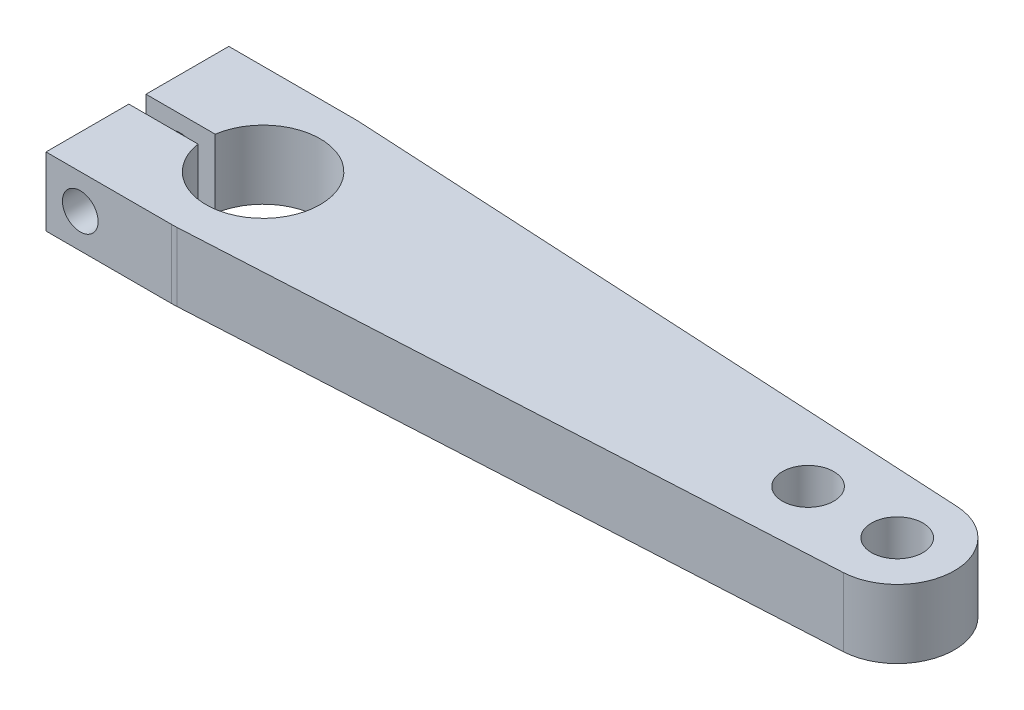
SolidWorks part; units mm, degrees
ref_plane "Alzado" through (0, 0, 0) normal (0, 0, 1) x (1, 0, 0)
ref_plane "Planta" through (0, 0, 0) normal (0, 1, 0) x (1, 0, 0)
ref_plane "Vista lateral" through (0, 0, 0) normal (1, 0, 0) x (0, 0, -1)
sketch "Croquis1" plane through (0, 0, 0) normal (0, 1, 0) x (1, 0, 0)
  line L0 (0.8649, 15.9766) -> (111.5405, 9.9854)
  line L1 (-22, 16) -> (0, 16)
  line L2 (-22, 16) -> (-22, -16)
  line L3 (-22, -16) -> (0, -16)
  line L5 (0.8649, -15.9766) -> (111.5405, -9.9854)
  circle A0 centre (0, 0) radius 10
  arc A1 (111.5405, -9.9854) -> (111.5405, 9.9854) centre (111, 0) ccw
  arc A2 (0.8649, 15.9766) -> (0, 16) centre (0, 0) ccw
  arc A3 (0, -16) -> (0.8649, -15.9766) centre (0, 0) ccw
  dimension "D3" = 20
  dimension "D5" = 10
  dimension "D1" = 16
  dimension "D2" = 16
  dimension "D4" = 22
  dimension "D6" = 111
extrude "Saliente-Extruir1" add sketch "Croquis1" along normal blind 12
sketch "Croquis2" plane through (0, 12, 0) normal (0, 1, 0) x (1, 0, 0)
  line L1 (-6.1165, 1.5) -> (-27.9498, 1.5)
  line L2 (-6.1165, 1.5) -> (-6.1165, -1.5)
  line L3 (-6.1165, -1.5) -> (-27.9498, -1.5)
  line L4 (-27.9498, 1.5) -> (-27.9498, -1.5)
  dimension "D1" = 1.5
  dimension "D2" = 1.5
extrude "Cortar-Extruir1" cut sketch "Croquis2" against normal blind 12
sketch "Croquis3" plane through (0, 0, 16) normal (0, 0, 1) x (1, 0, 0)
  line L0 (-22, 12) -> (-22, 0) construction
  line L1 (-22, 12) -> (0, 12) construction
  circle A0 centre (-16, 6) radius 3.125
  point P2 (-22, 6)
  dimension "D1" = 6.25
  dimension "D2" = 6
  dimension "D3" = 6
extrude "Cortar-Extruir2" cut sketch "Croquis3" against normal through all
sketch "Croquis6" plane through (0, 12, 0) normal (0, 1, 0) x (1, 0, 0)
  circle A0 centre (111, 0) radius 4.5
  circle A1 centre (95.4, 0) radius 4.5
  dimension "D1" = 9
  dimension "D2" = 9
  dimension "D3" = 15.6
extrude "Cortar-Extruir3" cut sketch "Croquis6" against normal up to next
